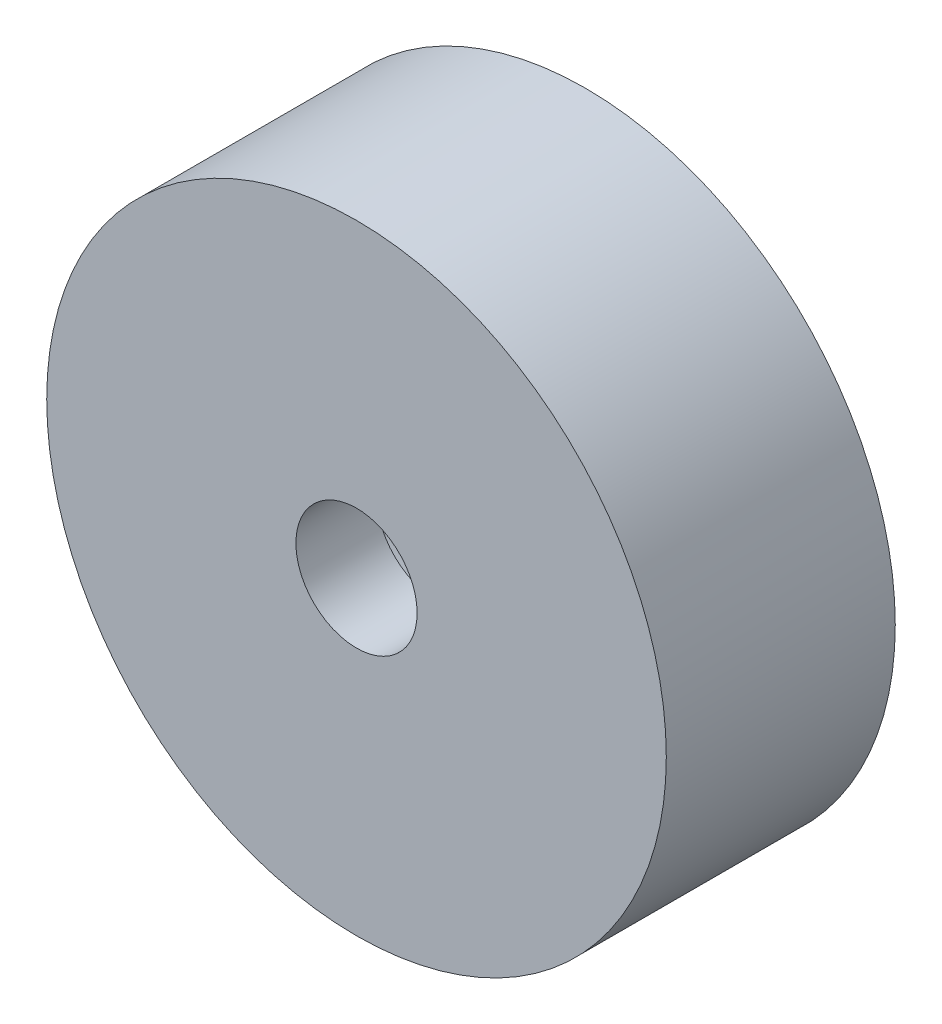
SolidWorks part; units mm, degrees
ref_plane "Front Plane" through (0, 0, 0) normal (0, 0, 1) x (1, 0, 0)
ref_plane "Top Plane" through (0, 0, 0) normal (0, 1, 0) x (1, 0, 0)
ref_plane "Right Plane" through (0, 0, 0) normal (1, 0, 0) x (0, 0, -1)
sketch "Sketch1" plane through (0, 0, 0) normal (0, 0, 1) x (1, 0, 0)
  circle A0 centre (0, 0) radius 9.5
  circle A1 centre (0, 0) radius 11.5
  dimension "D1" = 19
extrude "Boss-Extrude1" add sketch "Sketch1" along normal mid plane 7
sketch "Sketch2" plane through (0, 0, 3.5) normal (0, 0, 1) x (1, 0, 0)
  circle A0 centre (0, 0) radius 11.5 construction
  circle A1 centre (0, 0) radius 11.5
  circle A2 centre (0, 0) radius 2.25
  dimension "D1" = 4.5
extrude "Boss-Extrude2" add sketch "Sketch2" along normal mid plane 3
